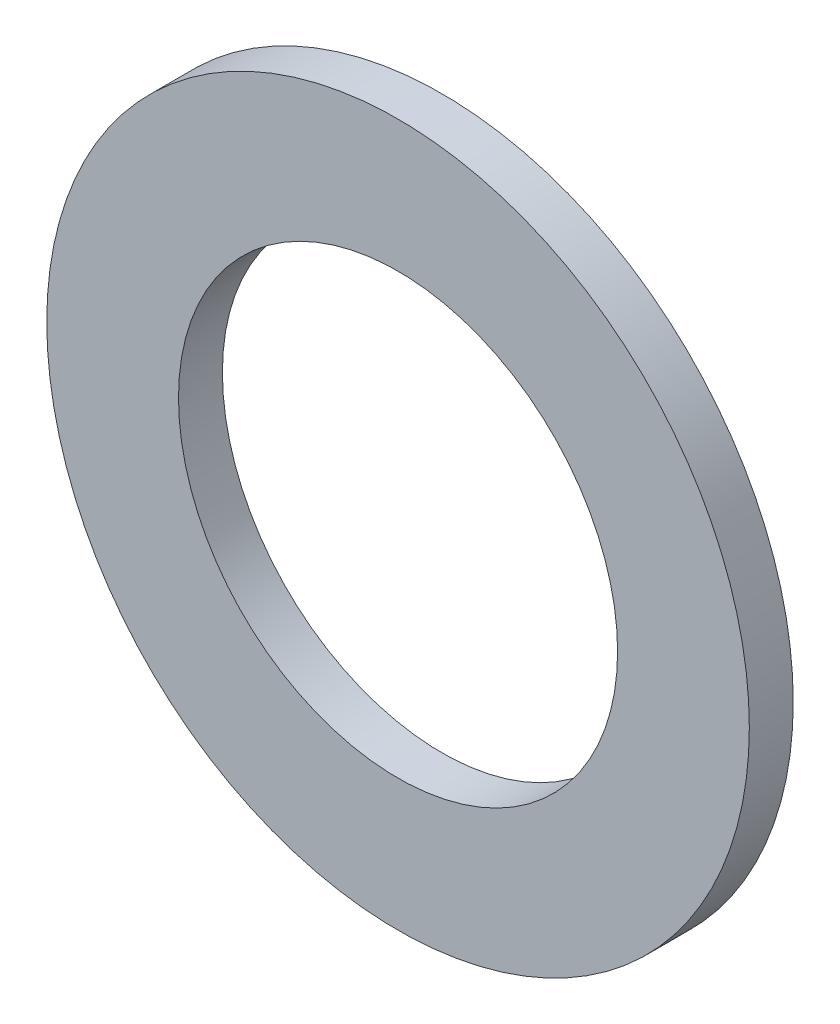
SolidWorks part; units mm, degrees
ref_plane "前视基准面" through (0, 0, 0) normal (0, 0, 1) x (1, 0, 0)
ref_plane "上视基准面" through (0, 0, 0) normal (0, 1, 0) x (1, 0, 0)
ref_plane "右视基准面" through (0, 0, 0) normal (1, 0, 0) x (0, 0, -1)
sketch "草图1" plane through (0, 0, 0) normal (0, 0, 1) x (1, 0, 0)
  circle A0 centre (0, 0) radius 8
  circle A1 centre (0, 0) radius 5
  dimension "D1" = 10
  dimension "D2" = 16
extrude "凸台-拉伸1" add sketch "草图1" along normal blind 1
